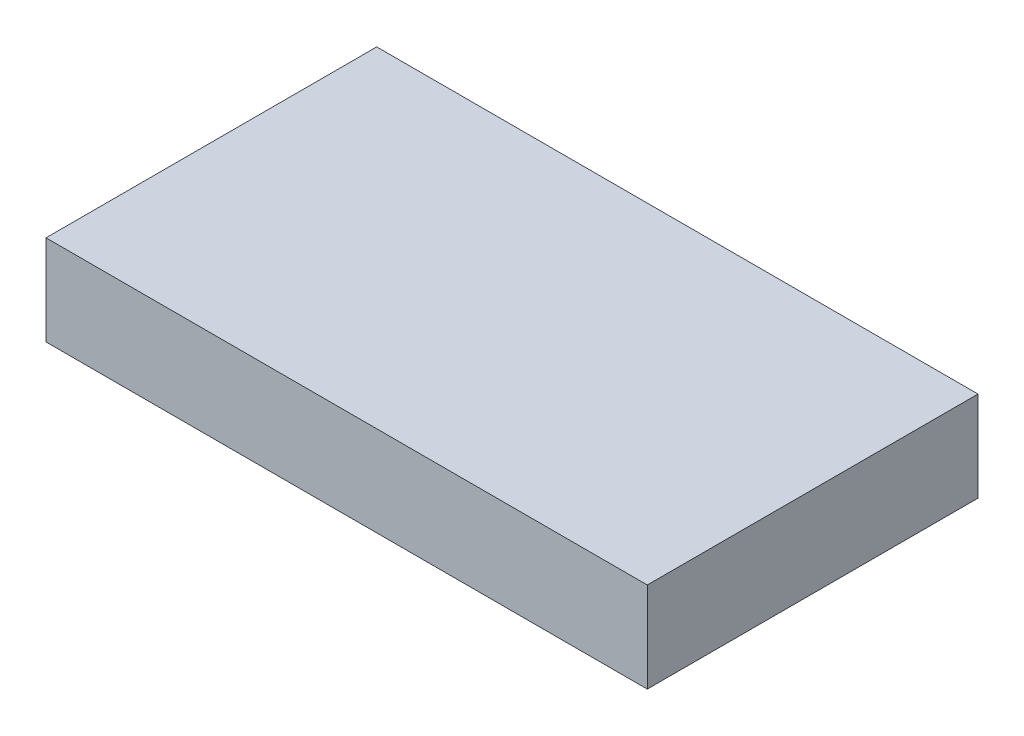
SolidWorks part; units mm, degrees
ref_plane "Front Plane" through (0, 0, 0) normal (0, 0, 1) x (1, 0, 0)
ref_plane "Top Plane" through (0, 0, 0) normal (0, 1, 0) x (1, 0, 0)
ref_plane "Right Plane" through (0, 0, 0) normal (1, 0, 0) x (0, 0, -1)
sketch "Sketch1" plane through (0, 0, 0) normal (0, 1, 0) x (1, 0, 0)
  line L0 (0, 0) -> (0, 55)
  line L1 (0, 55) -> (9, 55)
  line L2 (9, 55) -> (9, 25)
  line L3 (9, 25) -> (91, 25)
  line L4 (91, 25) -> (91, 55)
  line L5 (91, 55) -> (100, 55)
  line L6 (100, 55) -> (100, 0)
  line L7 (100, 0) -> (0, 0)
  dimension "D1" = 100
  dimension "D2" = 9
  dimension "D3" = 55
  dimension "D4" = 25
extrude "Boss-Extrude1" add sketch "Sketch1" along normal blind 10
sketch "Sketch2" plane through (0, 10, 0) normal (0, 1, 0) x (1, 0, 0)
  line L1 (0, 0) -> (100, 0)
  line L2 (0, 0) -> (0, 55)
  line L3 (0, 55) -> (100, 55)
  line L4 (100, 0) -> (100, 55)
extrude "Boss-Extrude2" add sketch "Sketch2" along normal blind 5
